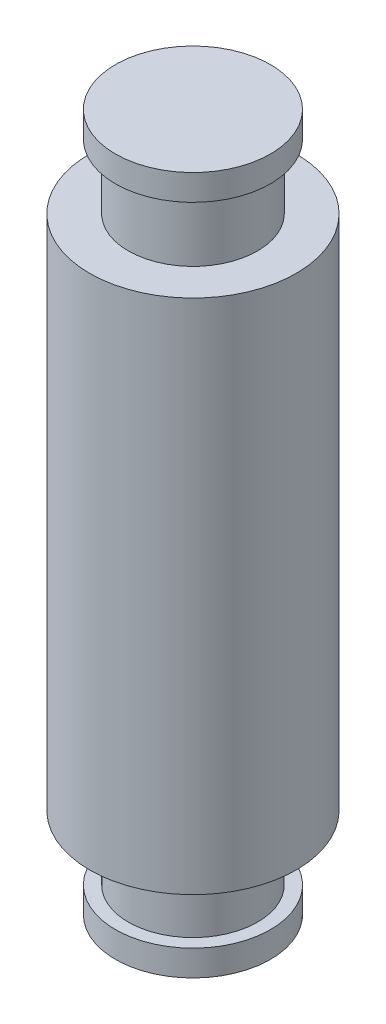
SolidWorks part; units mm, degrees
material "Titanium"
ref_plane "Front Plane" through (0, 0, 0) normal (0, 0, 1) x (1, 0, 0)
ref_plane "Top Plane" through (0, 0, 0) normal (0, 1, 0) x (1, 0, 0)
ref_plane "Right Plane" through (0, 0, 0) normal (1, 0, 0) x (0, 0, -1)
sketch "Sketch2" plane through (0, 0, 0) normal (0, 1, 0) x (1, 0, 0)
  circle A0 centre (0, 0) radius 4
extrude "Boss-Extrude2" add sketch "Sketch2" along normal blind 20
sketch "Sketch3" plane through (0, 0, 0) normal (0, -1, 0) x (1, 0, 0)
  circle A0 centre (0, 0) radius 2.5
extrude "Boss-Extrude3" add sketch "Sketch3" along normal blind 2.5
sketch "Sketch4" plane through (0, -2.5, 0) normal (0, -1, 0) x (1, 0, 0)
  circle A0 centre (0, 0) radius 3
extrude "Boss-Extrude4" add sketch "Sketch4" along normal blind 1
sketch "Sketch5" plane through (0, 20, 0) normal (0, 1, 0) x (1, 0, 0)
  circle A0 centre (0, 0) radius 2.5
extrude "Boss-Extrude5" add sketch "Sketch5" along normal blind 2.5
sketch "Sketch6" plane through (0, 22.5, 0) normal (0, 1, 0) x (1, 0, 0)
  circle A0 centre (0, 0) radius 3
extrude "Boss-Extrude7" add sketch "Sketch6" along normal blind 1
